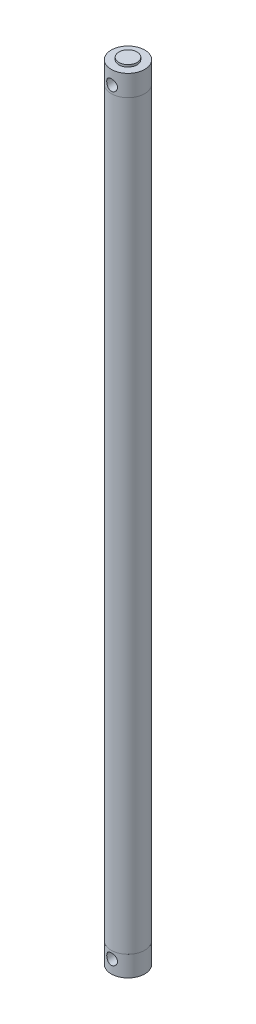
SolidWorks part; units mm, degrees
ref_plane "前视基准面" through (0, 0, 0) normal (0, 0, 1) x (1, 0, 0)
ref_plane "上视基准面" through (0, 0, 0) normal (0, 1, 0) x (1, 0, 0)
ref_plane "右视基准面" through (0, 0, 0) normal (1, 0, 0) x (0, 0, -1)
sketch "草图1" plane through (0, 0, 0) normal (0, 1, 0) x (1, 0, 0)
  circle A0 centre (0, 0) radius 15.5
  circle A1 centre (0, 0) radius 12.5
  dimension "D1" = 31
  dimension "D2" = 25
extrude "拉伸1" add sketch "草图1" along normal blind 686
sketch "草图2" plane through (0, 686, 0) normal (0, 1, 0) x (1, 0, 0)
  circle A0 centre (0, 0) radius 15.5
extrude "拉伸2" add sketch "草图2" along normal blind 19.5 separate body
sketch "草图3" plane through (0, 705.5, 0) normal (0, 1, 0) x (1, 0, 0)
  circle A0 centre (0, 0) radius 8.376
extrude "拉伸3" add sketch "草图3" along normal blind 2
sketch "草图4" plane through (0, 0, 0) normal (0, -1, 0) x (1, 0, 0)
  circle A0 centre (0, 0) radius 15.5
extrude "拉伸4" add sketch "草图4" along normal blind 19 separate body
sketch "草图5" plane through (0, -19, 0) normal (0, -1, 0) x (1, 0, 0)
  circle A0 centre (0, 0) radius 7
  dimension "D1" = 14
extrude "拉伸5" add sketch "草图5" along normal blind 1.5
sketch "草图6" plane through (0, -20.5, 0) normal (0, -1, 0) x (1, 0, 0)
  circle A0 centre (0, 0) radius 5
  dimension "D1" = 10
extrude "拉伸6" cut sketch "草图6" against normal up to next (20.5 mm away)
ref_plane "基准面1" through (0, 0, 15.5) normal (0, 0, 1) x (1, 0, 0)
sketch "草图7" plane through (0, 0, 15.5) normal (0, 0, 1) x (1, 0, 0)
  line L0 (15.5, 0) -> (-15.5, 0) construction
  line L1 (15.5, 686) -> (-15.5, 686) construction
  circle A0 centre (0, -7) radius 5
  circle A1 centre (0, 693) radius 5
  dimension "D1" = 10
  dimension "D3" = 10
  dimension "D2" = 7
  dimension "D4" = 7
extrude "拉伸7" cut sketch "草图7" against normal blind 15
sketch "草图8" plane through (0, -19, 0) normal (0, -1, 0) x (1, 0, 0)
  line L0 (-0.4171, 0) -> (17.4207, 0) construction
  line L1 (0, 0) -> (0, 14.02) construction
  circle A0 centre (-8.25, 8.25) radius 2.1
  circle A1 centre (8.25, 8.25) radius 2.1
  circle A2 centre (8.25, -8.25) radius 2.1
  circle A3 centre (-8.25, -8.25) radius 2.1
  dimension "D1" = 4.2
  dimension "D2" = 4.2
  dimension "D3" = 4.2
  dimension "D4" = 4.2
  dimension "D5" = 8.25
  dimension "D6" = 16.5
  dimension "D7" = 16.5
  dimension "D8" = 16.5
  dimension "D9" = 8.25
extrude "拉伸8" cut sketch "草图8" against normal blind 15
